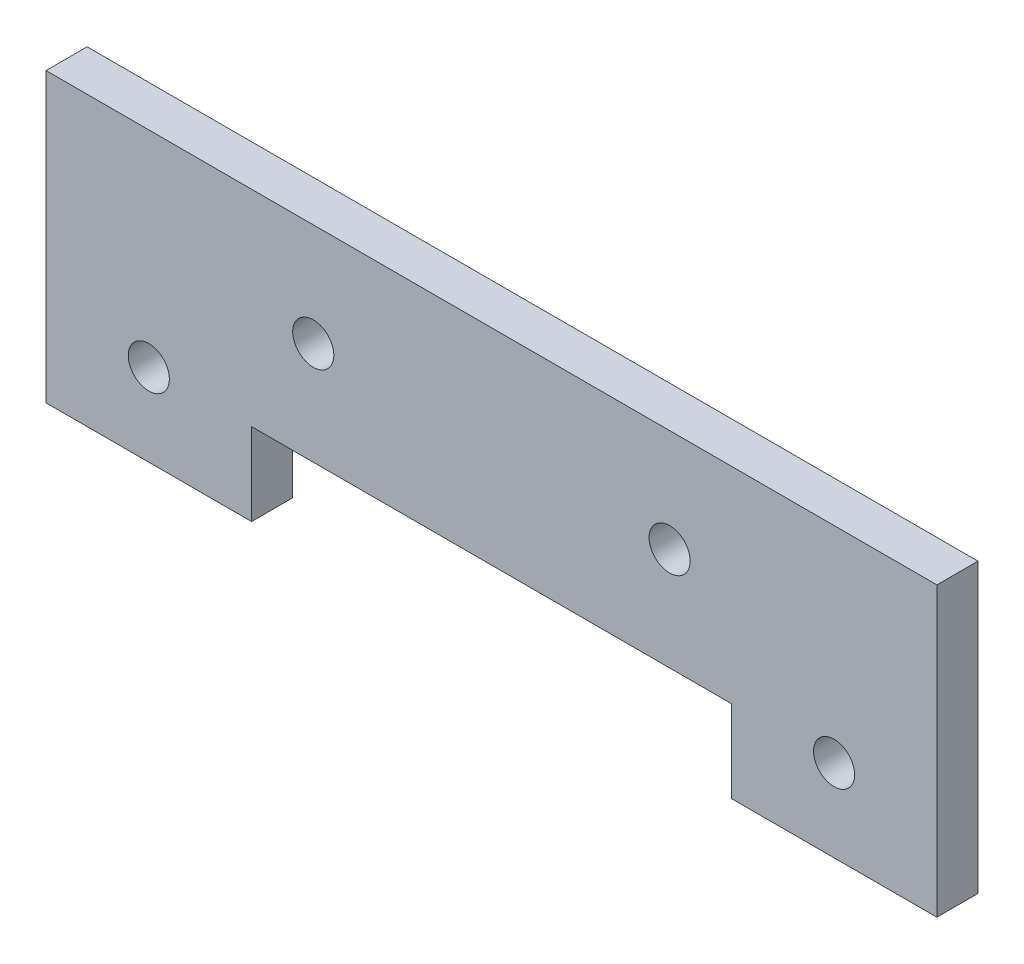
SolidWorks part; units mm, degrees
ref_plane "前视基准面" through (0, 0, 0) normal (0, 0, 1) x (1, 0, 0)
ref_plane "上视基准面" through (0, 0, 0) normal (0, 1, 0) x (1, 0, 0)
ref_plane "右视基准面" through (0, 0, 0) normal (1, 0, 0) x (0, 0, -1)
sketch "草图1" plane through (0, 0, 0) normal (0, 0, 1) x (1, 0, 0)
  line L0 (0, 0) -> (65, 0)
  line L1 (65, 0) -> (65, -21)
  line L2 (65, -21) -> (50, -21)
  line L3 (50, -21) -> (50, -15)
  line L4 (50, -15) -> (15, -15)
  line L5 (15, -15) -> (15, -21)
  line L6 (15, -21) -> (0, -21)
  line L7 (0, -21) -> (0, 0)
  dimension "D1" = 15
  dimension "D2" = 15
  dimension "D3" = 65
  dimension "D4" = 6
  dimension "D5" = 15
  dimension "D6" = 6
extrude "凸台-拉伸1" add sketch "草图1" along normal blind 3
sketch "草图2" plane through (0, 0, 3) normal (0, 0, 1) x (1, 0, 0)
  line L0 (65, 0) -> (0, 0) construction
  line L1 (65, -21) -> (65, 0) construction
  line L2 (0, 0) -> (0, -21) construction
  line L3 (0, -21) -> (15, -21) construction
  line L4 (50, -21) -> (65, -21) construction
  circle A0 centre (7.5, -15) radius 1.5
  circle A1 centre (57.5, -15) radius 1.5
  circle A2 centre (19.5, -7.5) radius 1.5
  circle A3 centre (45.5, -7.5) radius 1.5
  point P14 (0, 0)
  dimension "D1" = 3
  dimension "D2" = 7.5
  dimension "D3" = 7.5
  dimension "D4" = 7.5
  dimension "D5" = 6
  dimension "D6" = 6
  dimension "D7" = 12
  dimension "D8" = 12
extrude "切除-拉伸1" cut sketch "草图2" against normal blind 3
